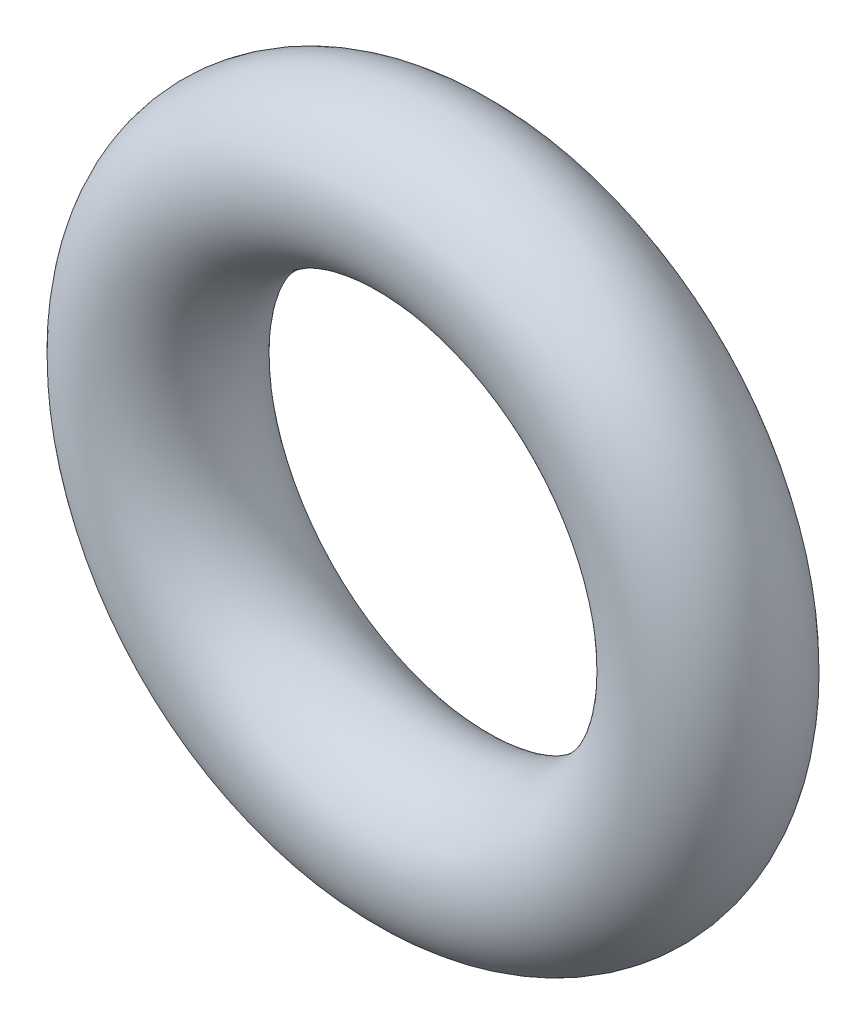
SolidWorks part; units mm, degrees
ref_plane "Front Plane" through (0, 0, 0) normal (0, 0, 1) x (1, 0, 0)
ref_plane "Top Plane" through (0, 0, 0) normal (0, 1, 0) x (1, 0, 0)
ref_plane "Right Plane" through (0, 0, 0) normal (1, 0, 0) x (0, 0, -1)
sketch "Sketch1" plane through (0, 0, 0) normal (0, 0, 1) x (1, 0, 0)
  line L0 (-2.25, 0) -> (2.25, 0) construction
  circle A0 centre (0, 0) radius 2.25
  circle A1 centre (0, 0) radius 1.25
  point P4 (1.25, 0)
  point P5 (2.25, 0)
  point P8 (0, 0)
  dimension "ID" = 2.5
  dimension "Width" = 1
  dimension "OD" = 4.5
sketch "Sketch2" plane through (0, 0, 0) normal (0, 1, 0) x (1, 0, 0)
  line L0 (-2.25, 0) -> (2.25, 0) construction
  line L1 (0, 0.5) -> (0, -0.5) construction
  circle A0 centre (1.75, 0) radius 0.5
  point P8 (0, 0)
  point P11 (1.75, 0.5)
revolve "Revolve1" add sketch "Sketch2" angle 360 about L1
sketch "Sketch3" plane through (0, 0, 0) normal (1, 0, 0) x (0, 0, -1)
  line L0 (-0.5, 0) -> (0.5, 0) construction
  line L1 (0.5, -1.75) -> (0.5, 1.75) construction
  point P2 (0, 0)
